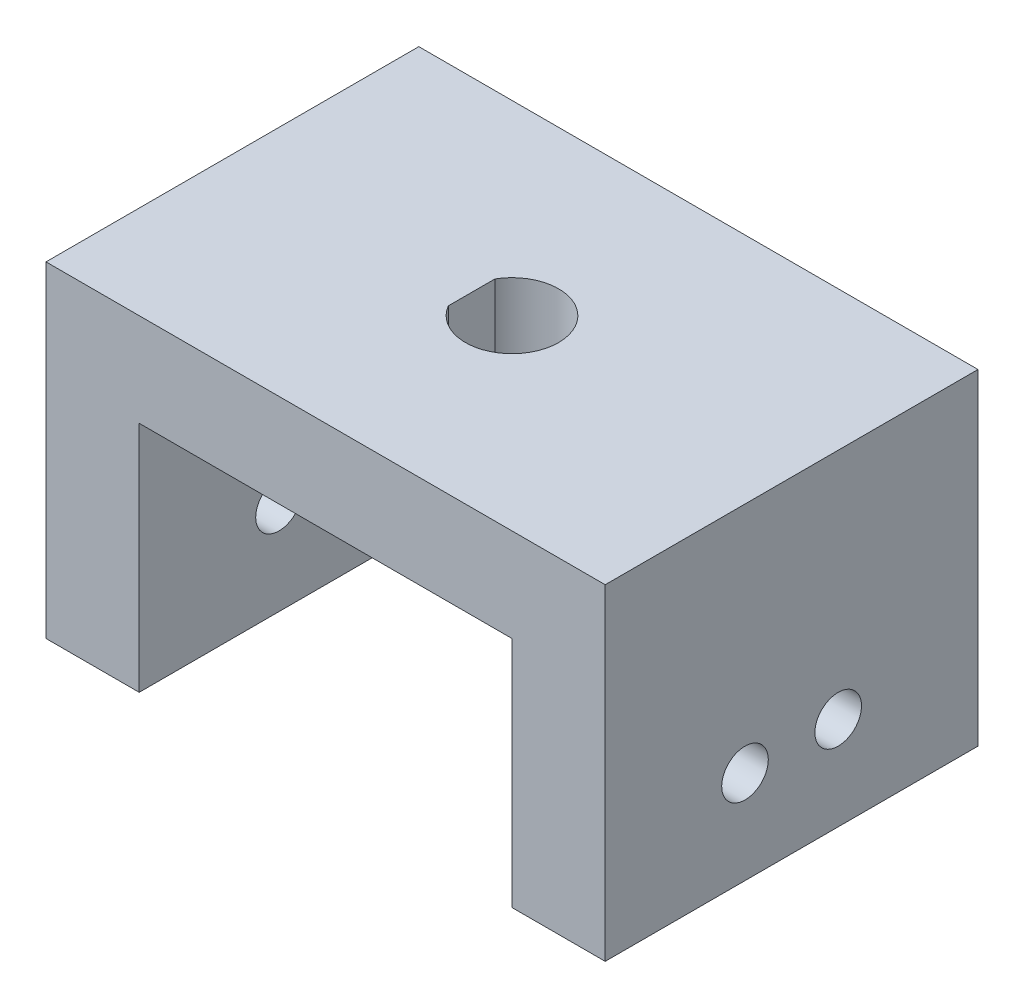
SolidWorks part; units mm, degrees
ref_plane "Front Plane" through (0, 0, 0) normal (0, 0, 1) x (1, 0, 0)
ref_plane "Top Plane" through (0, 0, 0) normal (0, 1, 0) x (1, 0, 0)
ref_plane "Right Plane" through (0, 0, 0) normal (1, 0, 0) x (0, 0, -1)
sketch "Sketch2" plane through (0, 0, 0) normal (0, 0, 1) x (1, 0, 0)
  line L0 (38.1, 0) -> (-38.1, 0)
  line L1 (-38.1, 0) -> (-38.1, -44.45)
  line L2 (-38.1, -44.45) -> (-25.4, -44.45)
  line L3 (-25.4, -44.45) -> (-25.4, -12.7)
  line L4 (-25.4, -12.7) -> (25.4, -12.7)
  line L5 (25.4, -12.7) -> (25.4, -44.45)
  line L6 (25.4, -44.45) -> (38.1, -44.45)
  line L7 (38.1, 0) -> (38.1, -44.45)
  point P4 (0, 0)
  dimension "D1" = 76.2
  dimension "D2" = 44.45
  dimension "D3" = 12.7
  dimension "D4" = 31.75
  dimension "D5" = 12.7
  dimension "D6" = 31.75
  dimension "D7" = 50.8
extrude "Boss-Extrude1" add sketch "Sketch2" along normal blind 50.8
sketch "Sketch3" plane through (0, 0, 0) normal (0, 1, 0) x (1, 0, 0)
  line L1 (-7.2007, -22.225) -> (-5.4993, -22.225)
  line L2 (-7.2007, -22.225) -> (-7.2007, -28.575)
  line L3 (-7.2007, -28.575) -> (-5.4993, -28.575)
  line L4 (-5.4993, -22.225) -> (-5.4993, -28.575)
  line L5 (-7.2007, -22.225) -> (-5.4993, -28.575) construction
  line L6 (-7.2007, -28.575) -> (-5.4993, -22.225) construction
  circle A0 centre (0, -25.4) radius 6.35
  point P2 (-6.35, -25.4)
  dimension "D1" = 12.7
  dimension "D2" = 6.35
extrude "Cut-Extrude1" cut sketch "Sketch3" against normal up to next contours L4 A0
sketch "Sketch4" plane through (-38.1, 0, 0) normal (-1, 0, 0) x (0, 0, 1)
  line L0 (0, -31.75) -> (50.8, -31.75) construction
  line L1 (0, 0) -> (0, -44.45) construction
  line L2 (50.8, 0) -> (50.8, -44.45) construction
  line L3 (25.4, 0) -> (25.4, -44.45) construction
  line L4 (50.8, 0) -> (0, 0) construction
  line L5 (50.8, -44.45) -> (0, -44.45) construction
  line L6 (0, -31.75) -> (0, -44.45) construction
  circle A0 centre (25.4, -31.75) radius 6.35 construction
  circle A1 centre (19.05, -31.75) radius 3.175
  circle A2 centre (31.75, -31.75) radius 3.175
  dimension "D2" = 12.7
  dimension "D3" = 6.35
  dimension "D4" = 6.35
  dimension "D1" = 12.7
extrude "Cut-Extrude2" cut sketch "Sketch4" against normal blind 83.8
